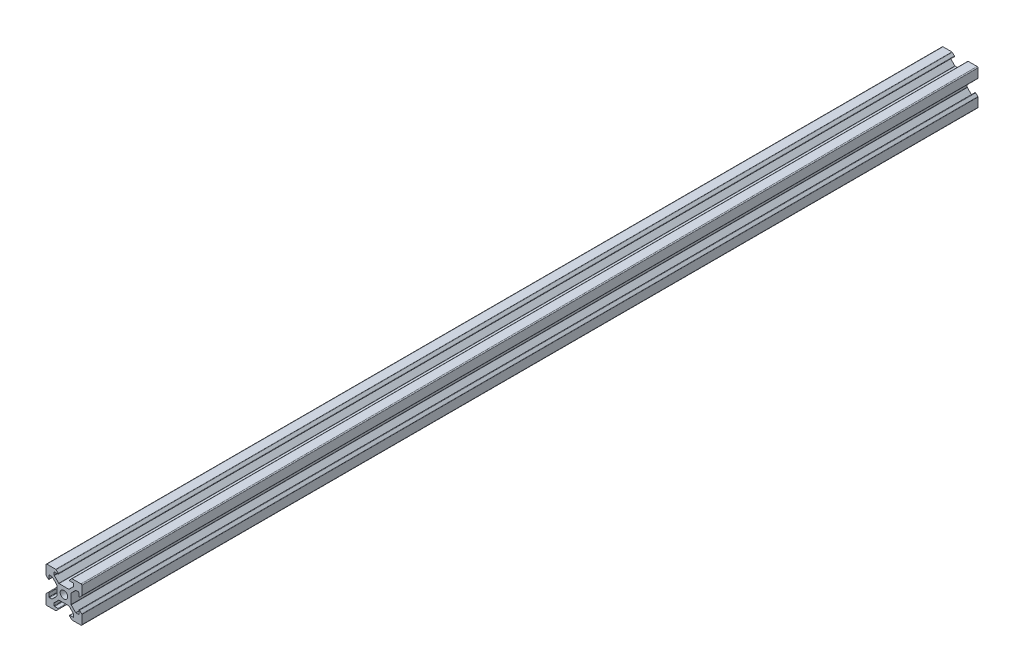
SolidWorks part; units mm, degrees
material "1060 Alloy"
ref_plane "Front Plane" through (0, 0, 0) normal (0, 0, 1) x (1, 0, 0)
ref_plane "Top Plane" through (0, 0, 0) normal (0, 1, 0) x (1, 0, 0)
ref_plane "Right Plane" through (0, 0, 0) normal (1, 0, 0) x (0, 0, -1)
sketch "Model" plane through (0, 0, 0) normal (0, 0, 1) x (1, 0, 0)
  line L0 (2012.9312, 1381.8004) -> (2012.9312, 1378.2004)
  line L1 (2016.4702, 1376.0004) -> (2017.3922, 1376.0004)
  line L2 (2020.9312, 1380.4614) -> (2020.9312, 1379.5394)
  line L3 (2016.4702, 1384.0004) -> (2017.3922, 1384.0004)
  line L270 (2012.9312, 1381.8004) -> (2012.9312, 1382.7004)
  line L271 (2012.8433, 1382.9125) -> (2010.3787, 1385.3772)
  line L272 (2010.2019, 1385.4504) -> (2008.8812, 1385.4504)
  line L273 (2008.6312, 1385.2004) -> (2008.6312, 1383.3504)
  line L274 (2008.2044, 1383.1736) -> (2007.0191, 1384.359)
  line L275 (2006.9312, 1384.5711) -> (2006.9312, 1389.5004)
  line L276 (2007.4312, 1390.0004) -> (2012.3605, 1390.0004)
  line L277 (2012.5726, 1389.9125) -> (2013.758, 1388.7272)
  line L278 (2013.5812, 1388.3004) -> (2011.7312, 1388.3004)
  line L279 (2011.4812, 1388.0504) -> (2011.4812, 1386.7297)
  line L280 (2011.5544, 1386.5529) -> (2014.0338, 1384.0736)
  line L281 (2014.2105, 1384.0004) -> (2016.4702, 1384.0004)
  line L282 (2017.3922, 1384.0004) -> (2019.6519, 1384.0004)
  line L283 (2019.8287, 1384.0736) -> (2022.308, 1386.5529)
  line L284 (2022.3812, 1386.7297) -> (2022.3812, 1388.0504)
  line L285 (2022.1312, 1388.3004) -> (2020.2812, 1388.3004)
  line L286 (2020.1044, 1388.7272) -> (2021.2898, 1389.9125)
  line L287 (2021.5019, 1390.0004) -> (2026.4312, 1390.0004)
  line L288 (2026.9312, 1389.5004) -> (2026.9312, 1384.5711)
  line L289 (2026.8433, 1384.359) -> (2025.658, 1383.1736)
  line L290 (2025.2312, 1383.3504) -> (2025.2312, 1385.2004)
  line L291 (2024.9812, 1385.4504) -> (2023.6605, 1385.4504)
  line L292 (2023.4838, 1385.3772) -> (2021.0044, 1382.8978)
  line L293 (2020.9312, 1382.7211) -> (2020.9312, 1380.4614)
  line L294 (2020.9312, 1379.5394) -> (2020.9312, 1377.2797)
  line L295 (2021.0044, 1377.1029) -> (2023.4838, 1374.6236)
  line L296 (2023.6605, 1374.5504) -> (2024.9812, 1374.5504)
  line L297 (2025.2312, 1374.8004) -> (2025.2312, 1376.6504)
  line L298 (2025.658, 1376.8272) -> (2026.8433, 1375.6418)
  line L299 (2026.9312, 1375.4297) -> (2026.9312, 1370.5004)
  line L300 (2026.4312, 1370.0004) -> (2021.5019, 1370.0004)
  line L301 (2021.2898, 1370.0883) -> (2020.1044, 1371.2736)
  line L302 (2020.2812, 1371.7004) -> (2022.1312, 1371.7004)
  line L303 (2022.3812, 1371.9504) -> (2022.3812, 1373.2711)
  line L304 (2022.308, 1373.4478) -> (2019.8287, 1375.9272)
  line L305 (2019.6519, 1376.0004) -> (2017.3922, 1376.0004)
  line L306 (2016.4702, 1376.0004) -> (2014.2105, 1376.0004)
  line L307 (2014.0338, 1375.9272) -> (2011.5544, 1373.4478)
  line L308 (2011.4812, 1373.2711) -> (2011.4812, 1371.9504)
  line L309 (2011.7312, 1371.7004) -> (2013.5812, 1371.7004)
  line L310 (2013.758, 1371.2736) -> (2012.5726, 1370.0883)
  line L311 (2012.3605, 1370.0004) -> (2007.4312, 1370.0004)
  line L312 (2006.9312, 1370.5004) -> (2006.9312, 1375.4297)
  line L313 (2007.0191, 1375.6418) -> (2008.2044, 1376.8272)
  line L314 (2008.6312, 1376.6504) -> (2008.6312, 1374.8004)
  line L315 (2008.8812, 1374.5504) -> (2010.2019, 1374.5504)
  line L316 (2010.3787, 1374.6236) -> (2012.8433, 1377.0883)
  line L317 (2012.9312, 1377.3004) -> (2012.9312, 1378.2004)
  circle A0 centre (2016.9312, 1380.0004) radius 2.1
  arc A427 (2012.9312, 1382.7004) -> (2012.8433, 1382.9125) centre (2012.6312, 1382.7004) ccw
  arc A428 (2010.3787, 1385.3772) -> (2010.2019, 1385.4504) centre (2010.2019, 1385.2004) ccw
  arc A429 (2008.8812, 1385.4504) -> (2008.6312, 1385.2004) centre (2008.8812, 1385.2004) ccw
  arc A430 (2008.2044, 1383.1736) -> (2008.6312, 1383.3504) centre (2008.3812, 1383.3504) ccw
  arc A431 (2006.9312, 1384.5711) -> (2007.0191, 1384.359) centre (2007.2312, 1384.5711) ccw
  arc A432 (2007.4312, 1390.0004) -> (2006.9312, 1389.5004) centre (2007.4312, 1389.5004) ccw
  arc A433 (2012.5726, 1389.9125) -> (2012.3605, 1390.0004) centre (2012.3605, 1389.7004) ccw
  arc A434 (2013.5812, 1388.3004) -> (2013.758, 1388.7272) centre (2013.5812, 1388.5504) ccw
  arc A435 (2011.7312, 1388.3004) -> (2011.4812, 1388.0504) centre (2011.7312, 1388.0504) ccw
  arc A436 (2011.4812, 1386.7297) -> (2011.5544, 1386.5529) centre (2011.7312, 1386.7297) ccw
  arc A437 (2014.0338, 1384.0736) -> (2014.2105, 1384.0004) centre (2014.2105, 1384.2504) ccw
  arc A441 (2019.6519, 1384.0004) -> (2019.8287, 1384.0736) centre (2019.6519, 1384.2504) ccw
  arc A442 (2022.308, 1386.5529) -> (2022.3812, 1386.7297) centre (2022.1312, 1386.7297) ccw
  arc A443 (2022.3812, 1388.0504) -> (2022.1312, 1388.3004) centre (2022.1312, 1388.0504) ccw
  arc A444 (2020.1044, 1388.7272) -> (2020.2812, 1388.3004) centre (2020.2812, 1388.5504) ccw
  arc A445 (2021.5019, 1390.0004) -> (2021.2898, 1389.9125) centre (2021.5019, 1389.7004) ccw
  arc A446 (2026.9312, 1389.5004) -> (2026.4312, 1390.0004) centre (2026.4312, 1389.5004) ccw
  arc A447 (2026.8433, 1384.359) -> (2026.9312, 1384.5711) centre (2026.6312, 1384.5711) ccw
  arc A448 (2025.2312, 1383.3504) -> (2025.658, 1383.1736) centre (2025.4812, 1383.3504) ccw
  arc A449 (2025.2312, 1385.2004) -> (2024.9812, 1385.4504) centre (2024.9812, 1385.2004) ccw
  arc A450 (2023.6605, 1385.4504) -> (2023.4838, 1385.3772) centre (2023.6605, 1385.2004) ccw
  arc A451 (2021.0044, 1382.8978) -> (2020.9312, 1382.7211) centre (2021.1812, 1382.7211) ccw
  arc A455 (2020.9312, 1377.2797) -> (2021.0044, 1377.1029) centre (2021.1812, 1377.2797) ccw
  arc A456 (2023.4838, 1374.6236) -> (2023.6605, 1374.5504) centre (2023.6605, 1374.8004) ccw
  arc A457 (2024.9812, 1374.5504) -> (2025.2312, 1374.8004) centre (2024.9812, 1374.8004) ccw
  arc A458 (2025.658, 1376.8272) -> (2025.2312, 1376.6504) centre (2025.4812, 1376.6504) ccw
  arc A459 (2026.9312, 1375.4297) -> (2026.8433, 1375.6418) centre (2026.6312, 1375.4297) ccw
  arc A460 (2026.4312, 1370.0004) -> (2026.9312, 1370.5004) centre (2026.4312, 1370.5004) ccw
  arc A461 (2021.2898, 1370.0883) -> (2021.5019, 1370.0004) centre (2021.5019, 1370.3004) ccw
  arc A462 (2020.2812, 1371.7004) -> (2020.1044, 1371.2736) centre (2020.2812, 1371.4504) ccw
  arc A463 (2022.1312, 1371.7004) -> (2022.3812, 1371.9504) centre (2022.1312, 1371.9504) ccw
  arc A464 (2022.3812, 1373.2711) -> (2022.308, 1373.4478) centre (2022.1312, 1373.2711) ccw
  arc A465 (2019.8287, 1375.9272) -> (2019.6519, 1376.0004) centre (2019.6519, 1375.7504) ccw
  arc A469 (2014.2105, 1376.0004) -> (2014.0338, 1375.9272) centre (2014.2105, 1375.7504) ccw
  arc A470 (2011.5544, 1373.4478) -> (2011.4812, 1373.2711) centre (2011.7312, 1373.2711) ccw
  arc A471 (2011.4812, 1371.9504) -> (2011.7312, 1371.7004) centre (2011.7312, 1371.9504) ccw
  arc A472 (2013.758, 1371.2736) -> (2013.5812, 1371.7004) centre (2013.5812, 1371.4504) ccw
  arc A473 (2012.3605, 1370.0004) -> (2012.5726, 1370.0883) centre (2012.3605, 1370.3004) ccw
  arc A474 (2006.9312, 1370.5004) -> (2007.4312, 1370.0004) centre (2007.4312, 1370.5004) ccw
  arc A475 (2007.0191, 1375.6418) -> (2006.9312, 1375.4297) centre (2007.2312, 1375.4297) ccw
  arc A476 (2008.6312, 1376.6504) -> (2008.2044, 1376.8272) centre (2008.3812, 1376.6504) ccw
  arc A477 (2008.6312, 1374.8004) -> (2008.8812, 1374.5504) centre (2008.8812, 1374.8004) ccw
  arc A478 (2010.2019, 1374.5504) -> (2010.3787, 1374.6236) centre (2010.2019, 1374.8004) ccw
  arc A479 (2012.8433, 1377.0883) -> (2012.9312, 1377.3004) centre (2012.6312, 1377.3004) ccw
extrude "Boss-Extrude1" add sketch "Model" along normal blind 500
